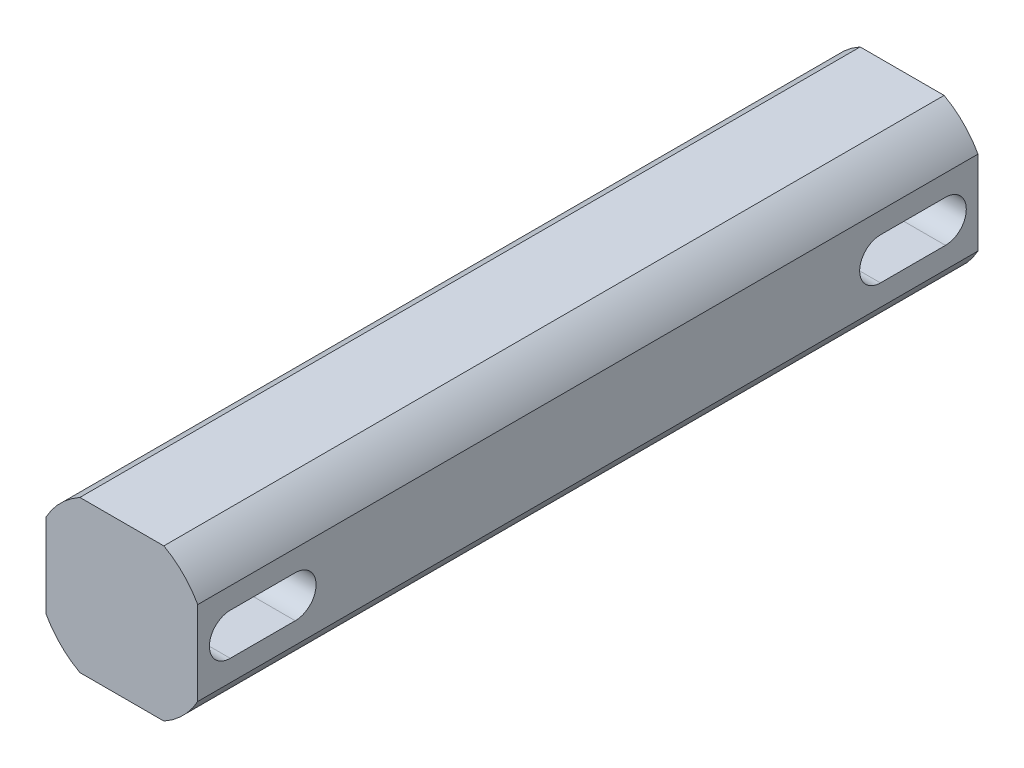
SolidWorks part; units mm, degrees
ref_plane "Front Plane" through (0, 0, 0) normal (0, 0, 1) x (1, 0, 0)
ref_plane "Top Plane" through (0, 0, 0) normal (0, 1, 0) x (1, 0, 0)
ref_plane "Right Plane" through (0, 0, 0) normal (1, 0, 0) x (0, 0, -1)
sketch "Sketch1" plane through (0, 0, 0) normal (0, 0, 1) x (1, 0, 0)
  circle A0 centre (0, 0) radius 6.35
  dimension "D1" = 12.7
extrude "Boss-Extrude1" add sketch "Sketch1" along normal mid plane 57.15
sketch "Sketch3" plane through (0, 0, 0) normal (0, 0, 1) x (1, 0, 0)
  line L1 (5.5563, -5.5562) -> (-5.5562, -5.5563)
  line L2 (5.5563, -5.5562) -> (5.5563, 5.5563)
  line L3 (5.5563, 5.5563) -> (-5.5562, 5.5562)
  line L4 (-5.5562, -5.5563) -> (-5.5562, 5.5562)
  line L5 (5.5563, -5.5562) -> (-5.5562, 5.5562) construction
  line L6 (5.5563, 5.5563) -> (-5.5562, -5.5563) construction
  point P0 (0, 0)
  dimension "D1" = 11.1125
extrude "Cut-Extrude1" cut sketch "Sketch3" against normal up to surface (28.575 mm away) and the other way up to surface (28.575 mm away) flip side to cut up to face at (6.35, 0, -28.575) other way up to face at (6.35, 0, 28.575)
sketch "Sketch4" plane through (-5.5562, 0, 0) normal (-1, 0, 0) x (0, 0, 1)
  line L0 (-26.1938, 0) -> (-21.4312, 0) construction
  line L1 (-26.1938, 1.524) -> (-21.4313, 1.524)
  line L2 (-26.1938, -1.524) -> (-21.4312, -1.524)
  line L3 (-28.575, 3.0742) -> (-28.575, -3.0742) construction
  line L4 (0, 3.0742) -> (0, -3.0742) construction
  line L5 (28.575, 3.0742) -> (-28.575, 3.0742) construction
  line L6 (-28.575, -3.0742) -> (28.575, -3.0742) construction
  line L7 (26.1938, 0) -> (21.4312, 0) construction
  line L8 (26.1938, 1.524) -> (21.4313, 1.524)
  line L9 (26.1938, -1.524) -> (21.4312, -1.524)
  arc A0 (-26.1938, 1.524) -> (-26.1938, -1.524) centre (-26.1938, 0) ccw
  arc A1 (-21.4312, -1.524) -> (-21.4313, 1.524) centre (-21.4312, 0) ccw
  arc A2 (26.1938, 1.524) -> (26.1938, -1.524) centre (26.1938, 0) cw
  arc A3 (21.4312, -1.524) -> (21.4313, 1.524) centre (21.4312, 0) cw
  point P3 (-23.8125, 0)
  point P10 (-28.575, 0)
  point P19 (23.8125, 0)
  dimension "D1" = 3.048
  dimension "D2" = 4.7625
  dimension "D3" = 4.7625
extrude "Cut-Extrude2" cut sketch "Sketch4" against normal up to next
